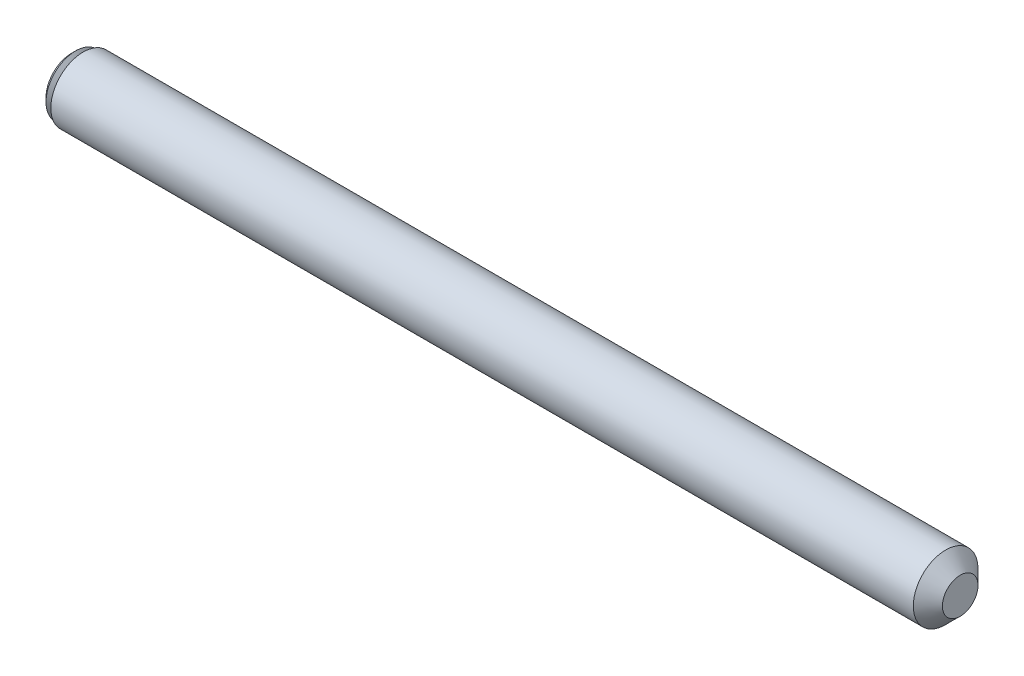
SolidWorks part; units mm, degrees
ref_plane "Plane1" through (0, 0, 0) normal (0, 0, 1) x (1, 0, 0)
ref_plane "Plane2" through (0, 0, 0) normal (0, 1, 0) x (1, 0, 0)
ref_plane "Plane3" through (0, 0, 0) normal (1, 0, 0) x (0, 0, -1)
sketch "BodySke" plane through (0, 0, 0) normal (0, 0, 1) x (1, 0, 0)
  line L0 (0, 0) -> (0, 3.1293)
  line L1 (0, 3.1293) -> (0.8395, 3.9688)
  line L2 (0.8395, 3.9688) -> (107.2156, 3.9688)
  line L3 (107.2156, 3.9688) -> (109, 2.1844)
  line L4 (109, 0) -> (0, 0)
  line L5 (-12.7, 0) -> (88.9, 0) construction
  line L6 (109, 2.1844) -> (109, 0)
  line L7 (109, 2.1844) -> (109, 11.7094) construction
  line L8 (0, -3.1293) -> (0.8395, -3.9688) construction
  line L9 (1.4097, 15.875) -> (1.4097, -3.175) construction
  line L10 (107.2156, -3.9688) -> (109, -2.1844) construction
  dimension "Length" = 109
  dimension "Diameter" = 7.9375
  dimension "Drive_ch_ang" = 45
  dimension "Minor_dia" = 6.2586
  dimension "Cup_nose_ang" = 45
  dimension "Cup_dia" = 4.3688
  dimension "Advance" = 1.4097
revolve "BaseBody" add sketch "BodySke" angle 360 about L5
cosmetic thread "ThreadCosmetic" parameters "Thread_minor"=6.2586
sketch "ThdSchSke" plane through (0, 0, 0) normal (0, 0, 1) x (1, 0, 0)
  line L0 (0.8395, -3.1293) -> (0.2517, -3.9688)
  line L1 (0.8395, -3.1293) -> (1.4273, -3.9688)
  line L2 (1.4273, -3.9688) -> (1.4273, -4.9609)
  line L3 (-3.175, 0) -> (5.1513, 0) construction
  line L4 (0.8395, 3.9688) -> (0.8395, -3.9688) construction
  line L5 (1.4273, -4.9609) -> (0.2517, -4.9609)
  line L6 (0.2517, -4.9609) -> (0.2517, -3.9688)
  dimension "Thread_minor" = 6.2586
  dimension "Diameter" = 7.9375
  dimension "SideAngle" = 55
  dimension "VeeAngle" = 70
  dimension "Overcut" = 9.9219
revolve "ThreadSchematic" cut sketch "ThdSchSke" angle 360 about L3
pattern_linear "ThdSchPat" [suppressed]
equation "\"Thread_minor@ThreadCosmetic\" = \"Minor_dia@BodySke\""
equation "\"Thread_minor@ThdSchSke\" = \"Thread_minor@ThreadCosmetic\""
equation "\"Diameter@ThdSchSke\" = \"Diameter@BodySke\""
equation "\"Overcut@ThdSchSke\" = \"Diameter@BodySke\" * 1.25"
equation "\"Num_threads@ThdSchPat\" = int( (\"Length@BodySke\" - ( ( ( \"Diameter@BodySke\" - \"Minor_dia@BodySke\" ) * 0.5 ) / tan( \"Drive_ch_ang@BodySke\" * 0.017453292 ) ) - ( ( ( \"Diameter@BodySke\" - \"Cup_dia@BodySke\" ) * 0.5 ) * tan( \"Cup_nose_ang@BodySke\" * 0.017453292 ) ) ) / \"Advance@BodySke\" + 0.999 )  + 1"
equation "\"Advance@ThdSchPat\" = (\"Length@BodySke\" - ( ( ( \"Diameter@BodySke\" - \"Minor_dia@BodySke\" ) * 0.5 ) / tan( \"Drive_ch_ang@BodySke\" * 0.017453292 ) ) - ( ( ( \"Diameter@BodySke\" - \"Cup_dia@BodySke\" ) * 0.5 ) * tan( \"Cup_nose_ang@BodySke\" * 0.017453292 ) ) ) /  (\"Num_threads@ThdSchPat\" - 1) 'relax it"
equation "' \"Num_threads@ThdSchPat\" = \"Num_threads@ThdSchPat\" - sgn( \"Num_threads@ThdSchPat\" - 1) '---chamfered tips only---"
